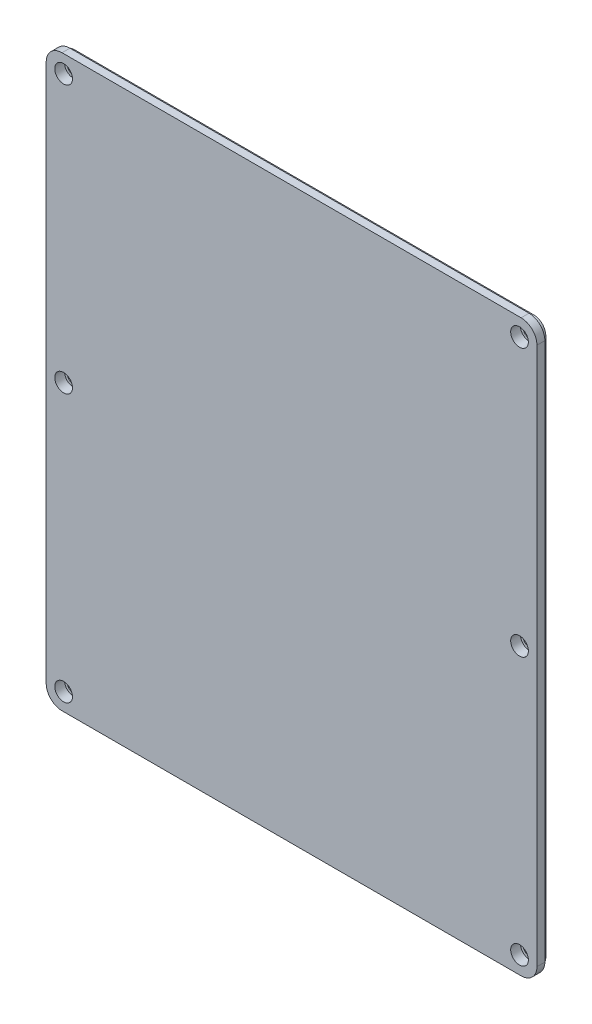
SolidWorks part; units mm, degrees
ref_plane "Front Plane" through (0, 0, 0) normal (0, 0, 1) x (1, 0, 0)
ref_plane "Top Plane" through (0, 0, 0) normal (0, 1, 0) x (1, 0, 0)
ref_plane "Right Plane" through (0, 0, 0) normal (1, 0, 0) x (0, 0, -1)
sketch "Sketch1" plane through (0, 0, 0) normal (0, 0, 1) x (1, 0, 0)
  line L1 (0, 0) -> (155, 0)
  line L2 (0, 0) -> (0, 180)
  line L3 (0, 180) -> (155, 180)
  line L4 (155, 0) -> (155, 180)
  dimension "D1" = 155
  dimension "D2" = 180
extrude "Boss-Extrude1" add sketch "Sketch1" along normal blind 4
fillet "Fillet1" radius 5 4 edges at (0, 0, 2) (155, 0, 2) (155, 180, 2) (0, 180, 2)
hole_wizard "Ø4.0mm Dowel Hole1" positions "Sketch2" profile "Sketch3" hole size "Ø4.0" standard "ISO"
sketch "Sketch2" plane through (0, 0, 0) normal (0, 0, -1) x (-1, 0, 0)
  point P0 (-60.95, 31.55)
  point P3 (-60.95, 61.55)
  point P6 (-61.95, 77.25)
  point P9 (-53.55, 107.55)
  point P16 (-61.95, 159.35)
  point P21 (-28.85, 107.55)
  point P25 (-22.6, 37.42)
  point P28 (-100.2, 19.55)
  point P31 (-98.45, 47.3)
  point P34 (-98.45, 75.05)
  point P38 (-110.45, 149.65)
  point P41 (-70.45, 149.65)
  point P57 (-70.45, 100.725)
  point P60 (-94.08, 100.725)
  point P64 (-148.75, 98.75)
  point P67 (-148.75, 127.85)
  point P70 (-148.75, 165.75)
  point P73 (-148.75, 136.65)
  point P76 (-141, 54.55)
  point P79 (-141, 34.05)
  point P82 (-137.55, 73.15)
  point P85 (-35.35, 50.5908)
  point P88 (-125.3554, 9.9448)
  point P90 (-141, 9.9448)
  point P92 (-141, 25.621)
  point P94 (-125.3554, 25.621)
  point P97 (0, 0)
  point P98 (0, 0)
  point P99 (0, 0)
  point P100 (-125.3554, 9.9448)
  point P101 (0, 0)
sketch "Sketch3" plane through (60.95, 31.55, 0) normal (1, 0, 0) x (0, 1, 0)
  line L0 (0, 0) -> (0, 3.1)
  line L1 (0, 3.1) -> (2, 3.1)
  line L2 (2, 3.1) -> (2, 0)
  line L5 (2, 0) -> (0, 0)
  line L10 (0, 3.1) -> (-2, 3.1) construction
  line L11 (0, -6.35) -> (0, 107.95) construction
  dimension "Hole Dia." = 4
  dimension "Hole Depth" = 3.1
sketch "Sketch4" plane through (0, 0, 0) normal (0, 0, -1) x (-1, 0, 0)
  line L0 (-77.5, 0) -> (-77.5, 180) construction
  line L1 (-5, 0) -> (-150, 0) construction
  line L2 (-150, 180) -> (-5, 180) construction
  line L3 (-5.5, 5.5) -> (-5.5, 0) construction
  line L4 (-5.5, 5.5) -> (0, 5.5) construction
  line L5 (0, 175) -> (0, 5) construction
  line L6 (-5.5, 174.5) -> (-5.5, 180) construction
  line L7 (-5.5, 174.5) -> (0, 174.5) construction
  line L8 (0, 90) -> (-155, 90) construction
  line L9 (-155, 5) -> (-155, 175) construction
  line L10 (-149.5, 174.5) -> (-155, 174.5) construction
  line L11 (-149.5, 174.5) -> (-149.5, 180) construction
  line L12 (-149.5, 5.5) -> (-155, 5.5) construction
  line L13 (-149.5, 5.5) -> (-149.5, 0) construction
  circle A0 centre (-5.5, 5.5) radius 1.95
  circle A1 centre (-5.5, 90) radius 1.95
  circle A2 centre (-5.5, 174.5) radius 1.95
  circle A3 centre (-149.5, 174.5) radius 1.95
  circle A4 centre (-149.5, 90) radius 1.95
  circle A5 centre (-149.5, 5.5) radius 1.95
  dimension "D1" = 3.9
  dimension "D2" = 5.5
extrude "Cut-Extrude1" cut sketch "Sketch4" against normal through all
sketch "Sketch5" plane through (0, 0, 4) normal (0, 0, 1) x (1, 0, 0)
  circle A0 centre (149.5, 5.5) radius 2.8
  circle A1 centre (149.5, 90) radius 2.8
  circle A2 centre (149.5, 174.5) radius 2.8
  circle A3 centre (5.5, 174.5) radius 2.8
  circle A4 centre (5.5, 90) radius 2.8
  circle A5 centre (5.5, 5.5) radius 2.8
  dimension "D1" = 5.6
extrude "Cut-Extrude2" cut sketch "Sketch5" against normal blind 3.1
sketch "Sketch6" plane through (0, 0, 0) normal (0, 0, -1) x (-1, 0, 0)
  line L8 (-150, 1.2) -> (-5, 1.2)
  line L9 (-1.2, 5) -> (-1.2, 175)
  line L10 (-5, 178.8) -> (-150, 178.8)
  line L11 (-153.8, 175) -> (-153.8, 5)
  line L12 (-150, 1.2) -> (-5, 1.2)
  line L13 (-1.2, 5) -> (-1.2, 175)
  line L14 (-5, 178.8) -> (-150, 178.8)
  line L15 (-153.8, 175) -> (-153.8, 5)
  line L16 (-150, 0) -> (-5, 0)
  line L17 (0, 5) -> (0, 175)
  line L18 (-5, 180) -> (-150, 180)
  line L19 (-155, 175) -> (-155, 5)
  line L20 (-150, 0) -> (-5, 0)
  line L21 (0, 5) -> (0, 175)
  line L22 (-5, 180) -> (-150, 180)
  line L23 (-155, 175) -> (-155, 5)
  arc A8 (-5, 1.2) -> (-1.2, 5) centre (-5, 5) ccw
  arc A9 (-1.2, 175) -> (-5, 178.8) centre (-5, 175) ccw
  arc A10 (-150, 178.8) -> (-153.8, 175) centre (-150, 175) ccw
  arc A11 (-153.8, 5) -> (-150, 1.2) centre (-150, 5) ccw
  arc A12 (-5, 1.2) -> (-1.2, 5) centre (-5, 5) ccw
  arc A13 (-1.2, 175) -> (-5, 178.8) centre (-5, 175) ccw
  arc A14 (-150, 178.8) -> (-153.8, 175) centre (-150, 175) ccw
  arc A15 (-153.8, 5) -> (-150, 1.2) centre (-150, 5) ccw
  arc A16 (-5, 0) -> (0, 5) centre (-5, 5) ccw
  arc A17 (0, 175) -> (-5, 180) centre (-5, 175) ccw
  arc A18 (-150, 180) -> (-155, 175) centre (-150, 175) ccw
  arc A19 (-155, 5) -> (-150, 0) centre (-150, 5) ccw
  arc A20 (-5, 0) -> (0, 5) centre (-5, 5) ccw
  arc A21 (0, 175) -> (-5, 180) centre (-5, 175) ccw
  arc A22 (-150, 180) -> (-155, 175) centre (-150, 175) ccw
  arc A23 (-155, 5) -> (-150, 0) centre (-150, 5) ccw
  dimension "D1" = 1.2
  dimension "D2" = 0
extrude "Cut-Extrude3" cut sketch "Sketch6" against normal blind 1.5
equation "\"Base Length\"= 180"
equation "\"Base Width\"= 155"
equation "\"D1@Sketch1\"=\"Base Width\""
equation "\"D2@Sketch1\"=\"Base Length\""
equation "\"Base Thickness\"= 4"
equation "\"D1@Boss-Extrude1\"=\"Base Thickness\""
